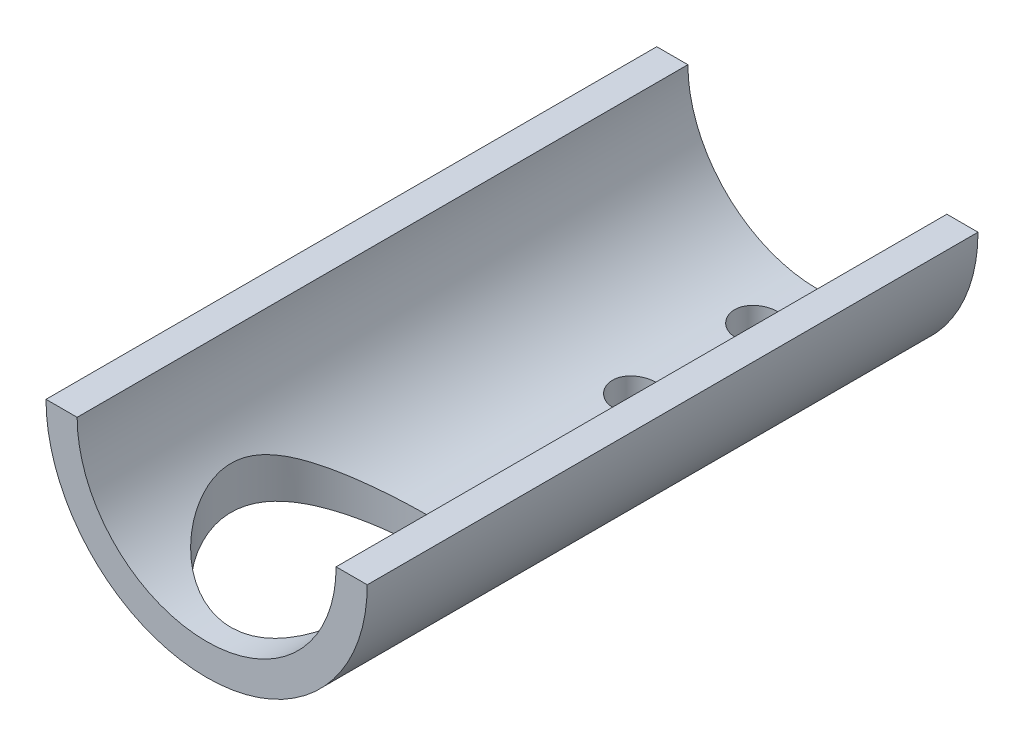
SolidWorks part; units mm, degrees
material "PVC Rigid"
ref_plane "Front Plane" through (0, 0, 0) normal (0, 0, 1) x (1, 0, 0)
ref_plane "Top Plane" through (0, 0, 0) normal (0, 1, 0) x (1, 0, 0)
ref_plane "Right Plane" through (0, 0, 0) normal (1, 0, 0) x (0, 0, -1)
sketch "Sketch1" plane through (0, 0, 0) normal (0, 0, 1) x (1, 0, 0)
  line L0 (-13.462, 0) -> (-16.7005, 0)
  line L1 (-16.7005, 0) -> (16.7005, 0)
  circle A0 centre (0, 0) radius 16.7005
  circle A1 centre (0, 0) radius 13.462
  dimension "D1" = 33.401
  dimension "D2" = 26.924
extrude "Boss-Extrude1" add sketch "Sketch1" along normal blind 63.5 contours A1 L0 A0 L1
sketch "Sketch2" plane through (0, 0, 0) normal (0, 1, 0) x (1, 0, 0)
  line L0 (-16.7005, 0) -> (16.7005, -63.5) construction
  line L1 (16.7005, -63.5) -> (-16.7005, -63.5) construction
  line L2 (-16.7005, -63.5) -> (16.7005, 0) construction
  line L3 (16.7005, 0) -> (-16.7005, 0) construction
  line L4 (-16.7005, 0) -> (0, 0) construction
  line L5 (0, 0) -> (0, -63.5) construction
  line L6 (-16.7005, -50.8) -> (16.7005, -50.8) construction
  line L7 (-16.7005, -63.5) -> (-16.7005, 0) construction
  line L8 (16.7005, -63.5) -> (16.7005, 0) construction
  circle A0 centre (0, -50.8) radius 10.16
  dimension "D2" = 20.32
  dimension "D1" = 12.7
extrude "Cut-Extrude1" cut sketch "Sketch2" against normal up to surface (16.7005 mm away)
sketch "Sketch3" [suppressed] plane through (0, 0, 63.5) normal (0, 0, 1) x (1, 0, 0)
  arc A0 (-13.462, 0) -> (13.462, 0) centre (0, 0) ccw construction
  point P0 (0, -13.462)
sketch "Sketch5" plane through (0, 0, 0) normal (0, 1, 0) x (1, 0, 0)
  line L0 (-16.7005, 0) -> (16.7005, 0) construction
  line L1 (-16.7005, -6.35) -> (16.7005, -6.35) construction
  line L2 (-16.7005, -12.7) -> (16.7005, -12.7) construction
  line L3 (-16.7005, -19.05) -> (16.7005, -19.05) construction
  line L4 (-16.7005, -25.4) -> (16.7005, -25.4) construction
  circle A0 centre (0, -6.35) radius 2.25
  circle A1 centre (0, -19.05) radius 2.25
  dimension "D2" = 4.5
  dimension "D3" = 4.5
  dimension "D1" = 5
extrude "Cut-Extrude2" cut sketch "Sketch5" against normal up to surface (16.7005 mm away)
sketch "Sketch6" [suppressed] plane through (0, 0, 63.5) normal (0, 0, 1) x (1, 0, 0)
  line L0 (-16.7005, 0) -> (0, -16.7005) construction
  line L1 (0, -16.7005) -> (-16.7005, -16.7005) construction
  line L2 (-16.7005, -16.7005) -> (16.7005, -16.7005) construction
  line L3 (16.7005, -16.7005) -> (0, -16.7005) construction
  line L4 (0, -16.7005) -> (16.7005, 0) construction
  arc A1 (-16.7005, 0) -> (16.7005, 0) centre (0, 0) ccw construction
ref_plane "Plane1" through (0, -17.78, 0) normal (0, 1, 0) x (1, 0, 0)
sketch "Sketch8" plane through (0, -17.78, 0) normal (0, 1, 0) x (1, 0, 0)
  line L0 (-16.7005, 0) -> (16.7005, 0) construction
  line L1 (-16.7005, -6.35) -> (16.7005, -6.35) construction
  line L2 (-16.7005, -12.7) -> (16.7005, -12.7) construction
  line L3 (-16.7005, -19.05) -> (16.7005, -19.05) construction
  line L4 (-16.7005, -25.4) -> (16.7005, -25.4) construction
  circle A0 centre (0, -6.35) radius 5
  circle A1 centre (0, -19.05) radius 5
  dimension "D2" = 10
  dimension "D3" = 10
  dimension "D1" = 5
extrude "Cut-Extrude4" cut sketch "Sketch8" along normal blind 2.032
